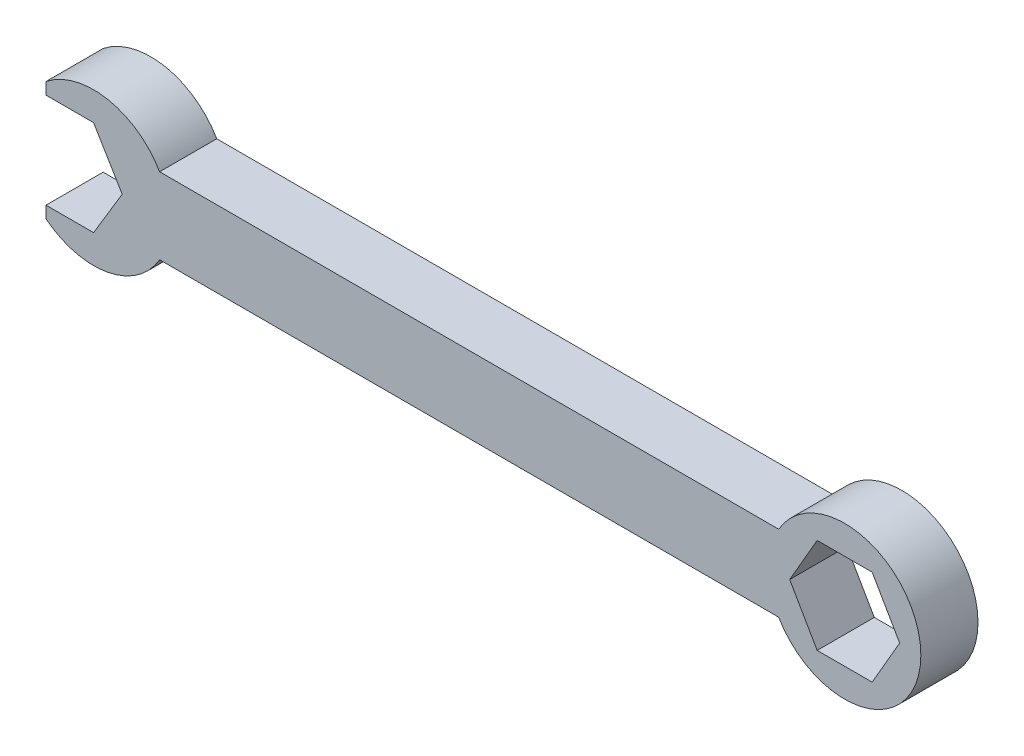
SolidWorks part; units mm, degrees
ref_plane "Front Plane" through (0, 0, 0) normal (0, 0, 1) x (1, 0, 0)
ref_plane "Top Plane" through (0, 0, 0) normal (0, 1, 0) x (1, 0, 0)
ref_plane "Right Plane" through (0, 0, 0) normal (1, 0, 0) x (0, 0, -1)
sketch "Sketch1" plane through (0, 0, 0) normal (0, 0, 1) x (1, 0, 0)
  line L7 (100.0038, 6.35) -> (92.6715, 6.35)
  line L14 (0, 0) -> (-3.81, 6.35)
  line L19 (-3.81, 6.35) -> (-10.16, 6.35)
  line L20 (19.9009, 0) -> (-19.9009, 0) construction
  line L21 (-3.81, -6.35) -> (-10.16, -6.35)
  line L22 (0, 0) -> (-3.81, -6.35)
  line L23 (-3.81, -993.65) -> (-3.81, 49006.35) construction
  line L24 (-10.16, 6.35) -> (-10.16, 7.9311)
  line L25 (-10.16, -6.35) -> (-10.16, -7.9311)
  line L26 (92.6715, 6.35) -> (89.0053, 0)
  line L27 (4.9888, 5.08) -> (87.5388, 5.08)
  line L29 (4.9888, -5.08) -> (87.5388, -5.08)
  line L31 (89.0053, 0) -> (92.6715, -6.35)
  line L32 (92.6715, -6.35) -> (100.0038, -6.35)
  line L33 (100.0038, -6.35) -> (103.67, 0)
  line L34 (103.67, 0) -> (100.0038, 6.35)
  arc A0 (-10.16, -7.9311) -> (4.9888, -5.08) centre (-3.81, 0) ccw
  arc A1 (4.9888, 5.08) -> (-10.16, 7.9311) centre (-3.81, 0) ccw
  arc A3 (87.5388, -5.08) -> (87.5388, 5.08) centre (96.3376, 0) ccw
  circle A4 centre (96.3376, 0) radius 6.35 construction
  point P12 (-3.81, 0)
  point P18 (0, 0)
  point P19 (0, 0)
  dimension "D1" = 20.32
  dimension "D8" = 20.32
  dimension "D2" = 10.16
  dimension "D3" = 6.35
  dimension "D4" = 12.7
  dimension "D5" = 5.08
  dimension "D6" = 10.16
  dimension "D7" = 82.55
  dimension "D9" = 12.7
  dimension "D10" = 10.16
extrude "Boss-Extrude1" add sketch "Sketch1" along normal blind 7.62
